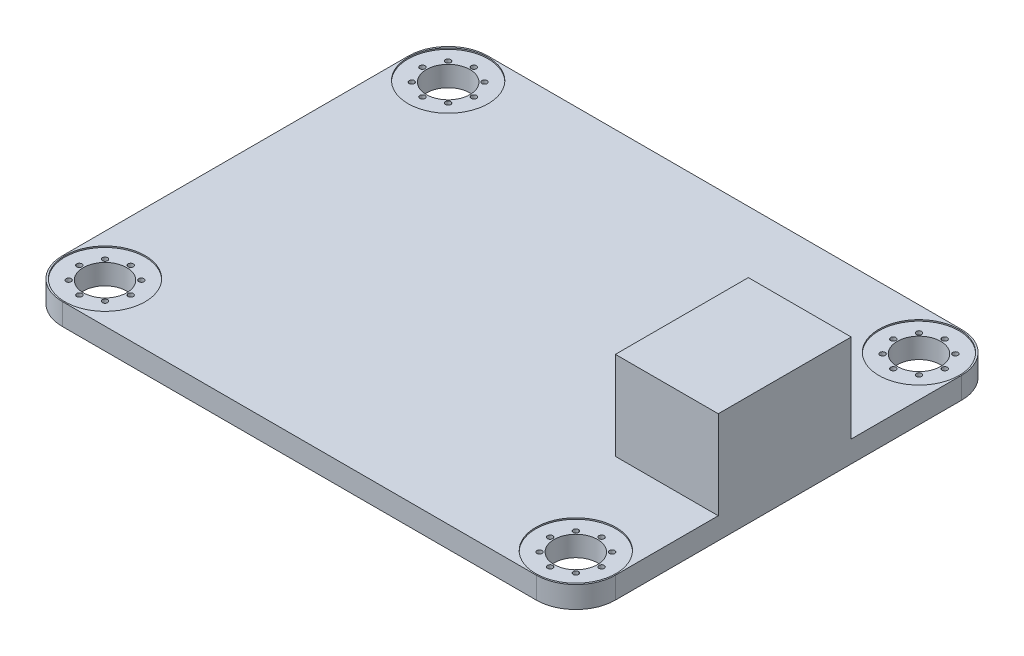
SolidWorks part; units mm, degrees
ref_plane "Alzado" through (0, 0, 0) normal (0, 0, 1) x (1, 0, 0)
ref_plane "Planta" through (0, 0, 0) normal (0, 1, 0) x (1, 0, 0)
ref_plane "Vista lateral" through (0, 0, 0) normal (1, 0, 0) x (0, 0, -1)
sketch "Croquis1" plane through (0, 0, 0) normal (0, 1, 0) x (1, 0, 0)
  line L0 (-20.97, 16.13) -> (-17.85, 16.13) construction
  line L1 (-20.97, 16.13) -> (20.97, 16.13)
  line L2 (-20.97, 16.13) -> (-20.97, -16.13)
  line L3 (-20.97, -16.13) -> (20.97, -16.13)
  line L4 (20.97, 16.13) -> (20.97, -16.13)
  line L5 (-20.97, 16.13) -> (20.97, -16.13) construction
  line L6 (-20.97, -16.13) -> (20.97, 16.13) construction
  line L7 (-17.85, 16.13) -> (-17.85, 14.66) construction
  line L8 (0, 16.13) -> (0, 22.9183) construction
  line L9 (-17.85, 14.66) -> (-17.85, 13.01) construction
  line L10 (-20.97, 0) -> (-36.4112, 0) construction
  line L11 (-17.85, 13.01) -> (-15.9, 13.01) construction
  circle A0 centre (-17.85, 13.01) radius 1.65
  circle A1 centre (17.85, 13.01) radius 1.65
  circle A2 centre (17.85, -13.01) radius 1.65
  circle A3 centre (-17.85, -13.01) radius 1.65
  circle A4 centre (-15.9, 13.01) radius 0.2
  circle A5 centre (-16.4711, 11.6311) radius 0.2
  circle A6 centre (-17.85, 11.06) radius 0.2
  circle A7 centre (-19.2289, 11.6311) radius 0.2
  circle A8 centre (-19.8, 13.01) radius 0.2
  circle A9 centre (-19.2289, 14.3889) radius 0.2
  circle A10 centre (-17.85, 14.96) radius 0.2
  circle A11 centre (-16.4711, 14.3889) radius 0.2
  circle A12 centre (19.8, 13.01) radius 0.2
  circle A13 centre (19.2289, 14.3889) radius 0.2
  circle A14 centre (17.85, 14.96) radius 0.2
  circle A15 centre (16.4711, 14.3889) radius 0.2
  circle A16 centre (15.9, 13.01) radius 0.2
  circle A17 centre (16.4711, 11.6311) radius 0.2
  circle A18 centre (19.2289, 11.6311) radius 0.2
  circle A19 centre (17.85, 11.06) radius 0.2
  circle A20 centre (19.2289, -11.6311) radius 0.2
  circle A21 centre (19.8, -13.01) radius 0.2
  circle A22 centre (19.2289, -14.3889) radius 0.2
  circle A23 centre (17.85, -14.96) radius 0.2
  circle A24 centre (16.4711, -14.3889) radius 0.2
  circle A25 centre (15.9, -13.01) radius 0.2
  circle A26 centre (17.85, -11.06) radius 0.2
  circle A27 centre (16.4711, -11.6311) radius 0.2
  circle A28 centre (-19.2289, -14.3889) radius 0.2
  circle A29 centre (-17.85, -14.96) radius 0.2
  circle A30 centre (-16.4711, -14.3889) radius 0.2
  circle A31 centre (-15.9, -13.01) radius 0.2
  circle A32 centre (-19.8, -13.01) radius 0.2
  circle A33 centre (-19.2289, -11.6311) radius 0.2
  circle A34 centre (-17.85, -11.06) radius 0.2
  circle A35 centre (-16.4711, -11.6311) radius 0.2
  point P0 (0, 0)
  point P38 (-17.85, 13.01)
  point P85 (0, 0)
  point P86 (0, 0)
  point P87 (-17.85, 13.01)
  dimension "D5" = 3.3
  dimension "D8" = 0.4
  dimension "D9" = 8
  dimension "D1" = 41.94
  dimension "D2" = 32.26
  dimension "D3" = 1.47
  dimension "D4" = 1.65
  dimension "D6" = 3.12
  dimension "D7" = 1.95
extrude "Saliente-Extruir1" add sketch "Croquis1" along normal blind 1.64
sketch "Croquis2" plane through (0, 1.64, 0) normal (0, 1, 0) x (1, 0, 0)
  line L0 (0, 16.13) -> (0, 23.3925) construction
  line L1 (20.97, 16.13) -> (-20.97, 16.13) construction
  line L2 (-20.97, 0) -> (-31.5872, 0) construction
  line L3 (-20.97, 16.13) -> (-20.97, -16.13) construction
  circle A0 centre (-17.85, 13.01) radius 3.04
  circle A1 centre (-17.85, 13.01) radius 1.65
  circle A2 centre (17.85, 13.01) radius 3.04
  circle A3 centre (17.85, 13.01) radius 1.65
  circle A4 centre (17.85, -13.01) radius 1.65
  circle A5 centre (17.85, -13.01) radius 3.04
  circle A6 centre (-17.85, -13.01) radius 1.65
  circle A7 centre (-17.85, -13.01) radius 3.04
  dimension "D1" = 6.08
extrude "Cortar-Extruir1" cut sketch "Croquis2" against normal blind 0.1
fillet "Redondeo2" radius 3 4 edges at (20.97, 0.82, 16.13) (20.97, 0.82, -16.13) (-20.97, 0.82, -16.13) (-20.97, 0.82, 16.13)
sketch "Croquis3" plane through (0, 1.64, 0) normal (0, 1, 0) x (1, 0, 0)
  line L0 (13.17, 16.13) -> (13.17, 4.75) construction
  line L1 (17.97, 16.13) -> (-17.97, 16.13) construction
  line L2 (13.17, 4.75) -> (20.97, 4.75) construction
  line L3 (20.97, -13.13) -> (20.97, 13.13) construction
  line L5 (13.17, 4.75) -> (20.97, 4.75)
  line L6 (13.17, 4.75) -> (13.17, -5.33)
  line L7 (13.17, -5.33) -> (20.97, -5.33)
  line L8 (20.97, 4.75) -> (20.97, -5.33)
  dimension "D1" = 11.38
  dimension "D2" = 7.8
  dimension "D3" = 10.08
extrude "Saliente-Extruir2" add sketch "Croquis3" along normal blind 6.7
sketch "Croquis4" plane through (20.97, 0, 0) normal (1, 0, 0) x (0, 0, -1)
  line L0 (-5.33, 8.34) -> (4.75, 1.64) construction
  line L1 (-5.33, 8.34) -> (4.75, 8.34)
  line L2 (-5.33, 8.34) -> (-5.33, 1.64)
  line L3 (-5.33, 1.64) -> (4.75, 1.64)
  line L4 (4.75, 8.34) -> (4.75, 1.64)
  line L5 (-5.33, 1.64) -> (4.75, 8.34) construction
  line L6 (4.75, 8.34) -> (3.95, 8.34) construction
  line L7 (3.15, 2.7) -> (-3.73, 2.7)
  line L8 (3.15, 2.7) -> (3.15, 7.28)
  line L9 (3.15, 7.28) -> (0.36, 7.28)
  line L10 (-3.73, 2.7) -> (-3.73, 7.28)
  line L11 (3.15, 2.7) -> (-3.73, 7.28) construction
  line L12 (3.15, 7.28) -> (-3.73, 2.7) construction
  line L13 (-0.94, 7.28) -> (-1.44, 7.78)
  line L14 (-1.44, 7.78) -> (0.86, 7.78)
  line L15 (-0.29, 8.34) -> (-0.29, 8.7429) construction
  line L16 (0.36, 7.28) -> (0.86, 7.78)
  line L17 (-0.94, 7.28) -> (-3.73, 7.28)
  line L18 (3.95, 7.54) -> (3.95, 5.32)
  line L20 (3.95, 8.34) -> (3.95, 7.54)
  point P6 (-0.29, 4.99)
  point P19 (-0.29, 7.78)
  dimension "D1" = 1.06
  dimension "D2" = 0.8
  dimension "D3" = 0.65
  dimension "D4" = 0.5
  dimension "D5" = 0.5
  dimension "D6" = 0.8
  dimension "D7" = 0.8
  dimension "D8" = 2.22
